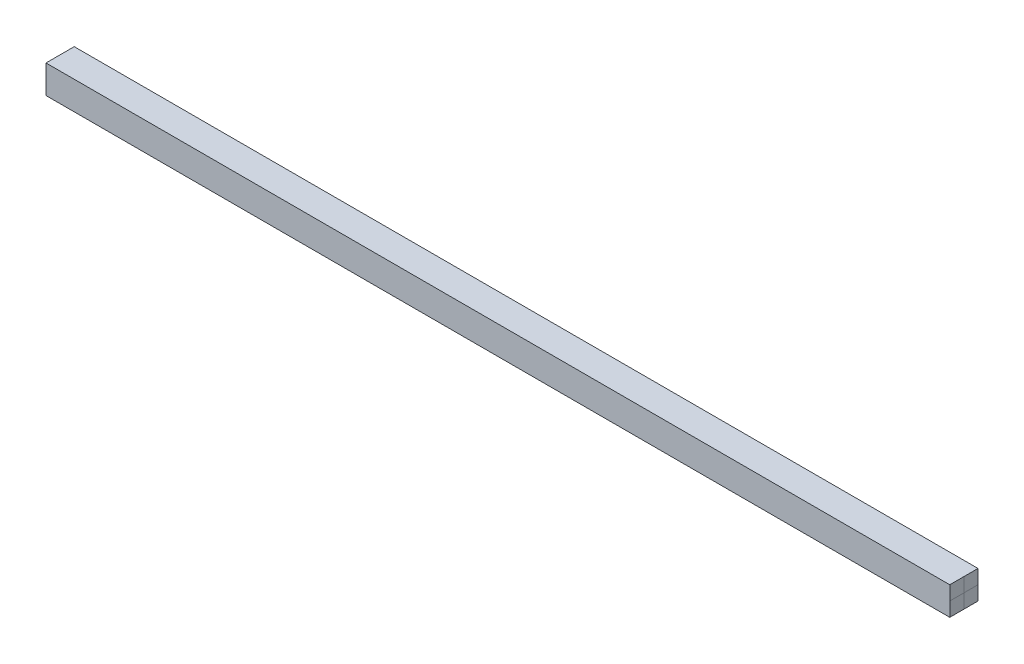
SolidWorks part; units mm, degrees
ref_plane "Front Plane" through (0, 0, 0) normal (0, 0, 1) x (1, 0, 0)
ref_plane "Top Plane" through (0, 0, 0) normal (0, 1, 0) x (1, 0, 0)
ref_plane "Right Plane" through (0, 0, 0) normal (1, 0, 0) x (0, 0, -1)
other "Configuration Table"
sketch "Sketch6" plane through (0, 0, 0) normal (1, 0, 0) x (0, 0, -1)
  line L1 (50, -50) -> (-50, -50)
  line L2 (50, -50) -> (50, 50)
  line L3 (50, 50) -> (-50, 50)
  line L4 (-50, -50) -> (-50, 50)
  line L5 (50, -50) -> (-50, 50) construction
  line L6 (50, 50) -> (-50, -50) construction
  point P0 (0, 0)
  dimension "D1" = 100
  dimension "D2" = 100
extrude "Extrude2" add sketch "Sketch6" along normal blind 3200
sketch "Sketch7" plane through (3200, 0, 0) normal (1, 0, 0) x (0, 0, -1)
  line L0 (-53.0288, 0) -> (54.1095, 0)
split line "Split Line1" [suppressed]
sketch "Sketch8" plane through (3200, 0, 0) normal (1, 0, 0) x (0, 0, -1)
  line L0 (-62.2391, 0) -> (62.3729, 0)
split line "Split Line2"
sketch "Sketch9" plane through (3200, 0, 0) normal (1, 0, 0) x (0, 0, -1)
  line L0 (0, -63.5018) -> (0, 67.9735)
split line "Split Line3"
